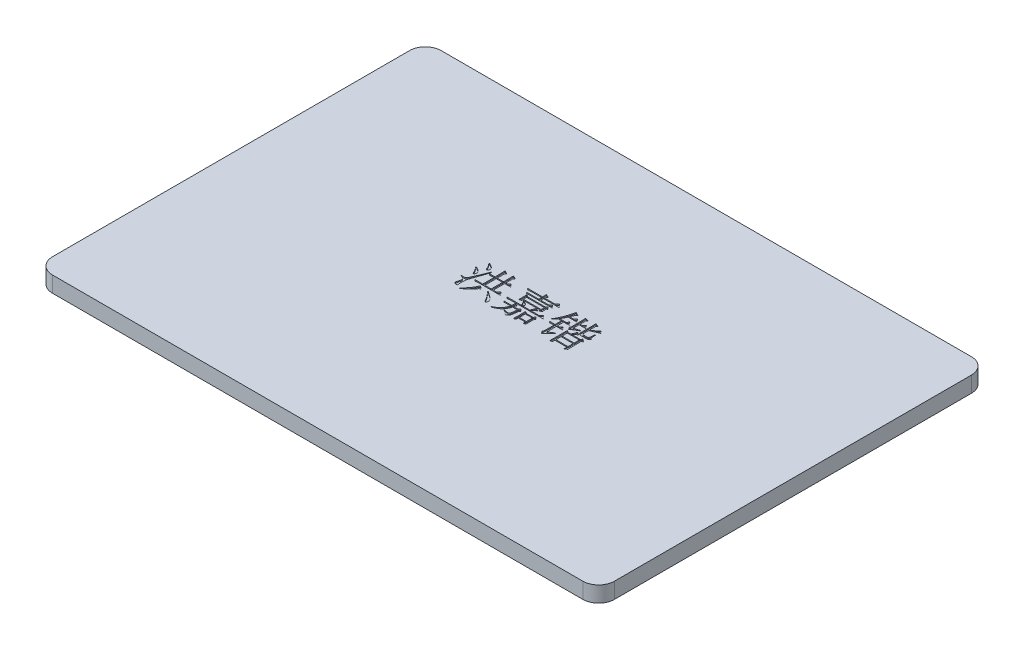
SolidWorks part; units mm, degrees
ref_plane "前视基准面" through (0, 0, 0) normal (0, 0, 1) x (1, 0, 0)
ref_plane "上视基准面" through (0, 0, 0) normal (0, 1, 0) x (1, 0, 0)
ref_plane "右视基准面" through (0, 0, 0) normal (1, 0, 0) x (0, 0, -1)
other "Configuration Table"
sketch "草图1" plane through (0, 0, 0) normal (0, 1, 0) x (1, 0, 0)
  line L1 (-177.6124, -122.85) -> (177.6124, -122.85)
  line L2 (-177.6124, -122.85) -> (-177.6124, 122.85)
  line L3 (-177.6124, 122.85) -> (177.6124, 122.85)
  line L4 (177.6124, -122.85) -> (177.6124, 122.85)
  line L5 (-177.6124, -122.85) -> (177.6124, 122.85) construction
  line L6 (-177.6124, 122.85) -> (177.6124, -122.85) construction
  point P0 (0, 0)
  dimension "D1" = 355.2247
  dimension "D2" = 245.7
extrude "凸台-拉伸1" add sketch "草图1" along normal blind 10 contours L4 L3 L2 L1
fillet "圆角1" radius 10 4 edges at (177.6124, 5, 122.85) (-177.6124, 5, 122.85) (-177.6124, 5, -122.85) (177.6124, 5, -122.85)
sketch "草图5" plane through (0, 10, 0) normal (0, 1, 0) x (1, 0, 0)
  line L0 (-177.6124, 1.5776) -> (177.6124, 0) construction
  line L1 (-177.6124, -112.85) -> (-177.6124, 112.85) construction
  line L2 (177.6124, -112.85) -> (177.6124, 112.85) construction
  text T0 "洪嘉锴" font "Century Gothic" height in points 72
extrude "切除-拉伸2" cut sketch "草图5" against normal blind 0.7
